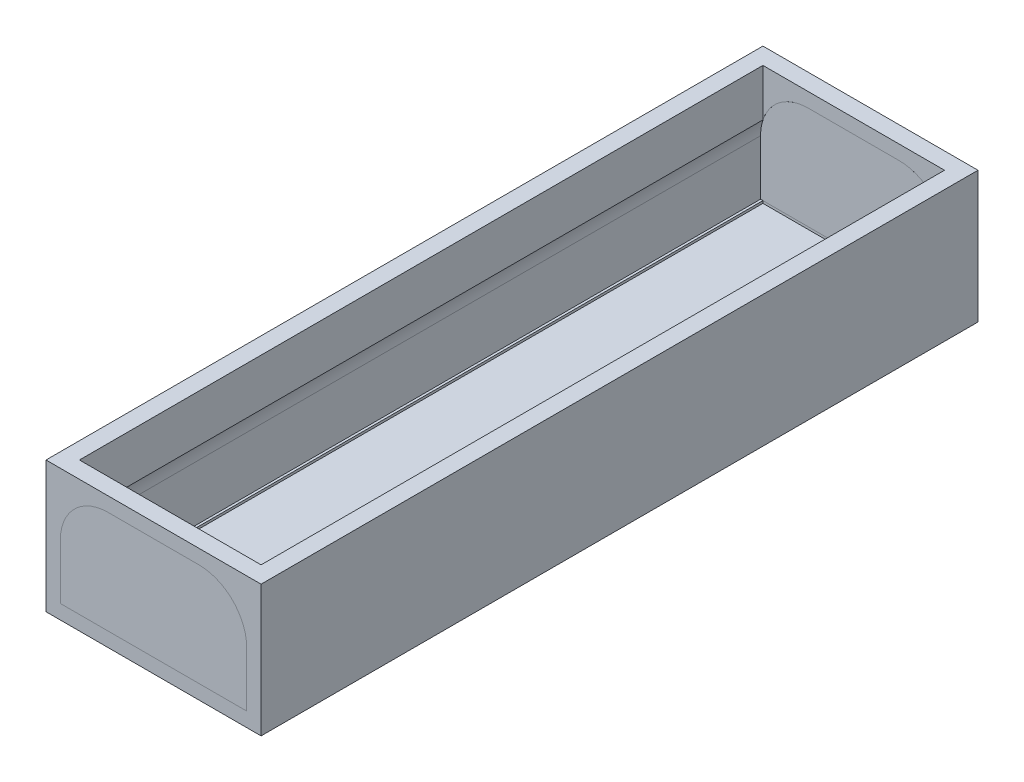
SolidWorks part; units mm, degrees
other "drawer"
ref_plane "Front Plane" through (0, 0, 0) normal (0, 0, 1) x (1, 0, 0)
ref_plane "Top Plane" through (0, 0, 0) normal (0, 1, 0) x (1, 0, 0)
ref_plane "Right Plane" through (0, 0, 0) normal (1, 0, 0) x (0, 0, -1)
sketch "Esquisse1" plane through (0, 0, 0) normal (0, 0, 1) x (1, 0, 0)
  line L1 (45, -27.5) -> (-45, -27.5)
  line L2 (45, -27.5) -> (45, 27.5)
  line L3 (45, 27.5) -> (-45, 27.5)
  line L4 (-45, -27.5) -> (-45, 27.5)
  line L5 (45, -27.5) -> (-45, 27.5) construction
  line L6 (45, 27.5) -> (-45, -27.5) construction
  point P0 (0, 0)
  dimension "D1" = 55
  dimension "D2" = 90
extrude "Boss.-Extru.1" add sketch "Esquisse1" along normal blind 300
sketch "Esquisse3" plane through (0, 27.5, 0) normal (0, 1, 0) x (1, 0, 0)
  line L8 (38, -7) -> (-38, -7)
  line L9 (-38, -7) -> (-38, -293)
  line L10 (-38, -293) -> (38, -293)
  line L11 (38, -293) -> (38, -7)
  line L12 (38, -7) -> (-38, -7)
  line L13 (-38, -7) -> (-38, -293)
  line L14 (-38, -293) -> (38, -293)
  line L15 (38, -293) -> (38, -7)
  dimension "D1" = 7
extrude "Enlèv. mat.-Extru.1" cut sketch "Esquisse3" against normal blind 50
sketch "Esquisse4" plane through (0, 0, 300) normal (0, 0, 1) x (1, 0, 0)
  line L8 (-39, 21.5) -> (-39, -21.5)
  line L9 (-39, -21.5) -> (39, -21.5)
  line L10 (39, -21.5) -> (39, 21.5)
  line L11 (39, 21.5) -> (-39, 21.5)
  line L12 (-39, 1.5) -> (-39, -21.5)
  line L13 (-39, -21.5) -> (39, -21.5)
  line L14 (39, -21.5) -> (39, 1.5)
  line L15 (19, 21.5) -> (-19, 21.5)
  arc A0 (39, 1.5) -> (19, 21.5) centre (19, 1.5) ccw
  arc A1 (-39, 1.5) -> (-19, 21.5) centre (-19, 1.5) cw
  dimension "D2" = 20
  dimension "D1" = 6
extrude "Enlèv. mat.-Extru.2" cut sketch "Esquisse4" against normal blind 475
sketch "Esquisse5" plane through (0, 0, 300) normal (0, 0, 1) x (1, 0, 0)
  line L4 (-39, 1.5) -> (-39, -21.5) construction
  line L5 (-39, -21.5) -> (39, -21.5) construction
  line L6 (39, -21.5) -> (39, 1.5) construction
  line L7 (19, 21.5) -> (-19, 21.5) construction
  line L8 (-39, 1.5) -> (-39, -21.5)
  line L9 (-39, -21.5) -> (39, -21.5)
  line L10 (39, -21.5) -> (39, 1.5)
  line L11 (19, 21.5) -> (-19, 21.5)
  arc A0 (39, 1.5) -> (19, 21.5) centre (19, 1.5) ccw construction
  arc A1 (-19, 21.5) -> (-39, 1.5) centre (-19, 1.5) ccw construction
  arc A2 (39, 1.5) -> (19, 21.5) centre (19, 1.5) ccw
  arc A3 (-19, 21.5) -> (-39, 1.5) centre (-19, 1.5) ccw
extrude "Boss.-Extru.2" add sketch "Esquisse5" against normal blind 5 separate body
ref_plane "Plan1" through (0, 0, 151) normal (0, 0, -1) x (-1, 0, 0)
mirror "Symétrie2" about plane through (0, 0, 151) normal (0, 0, -1) of bodies 104
